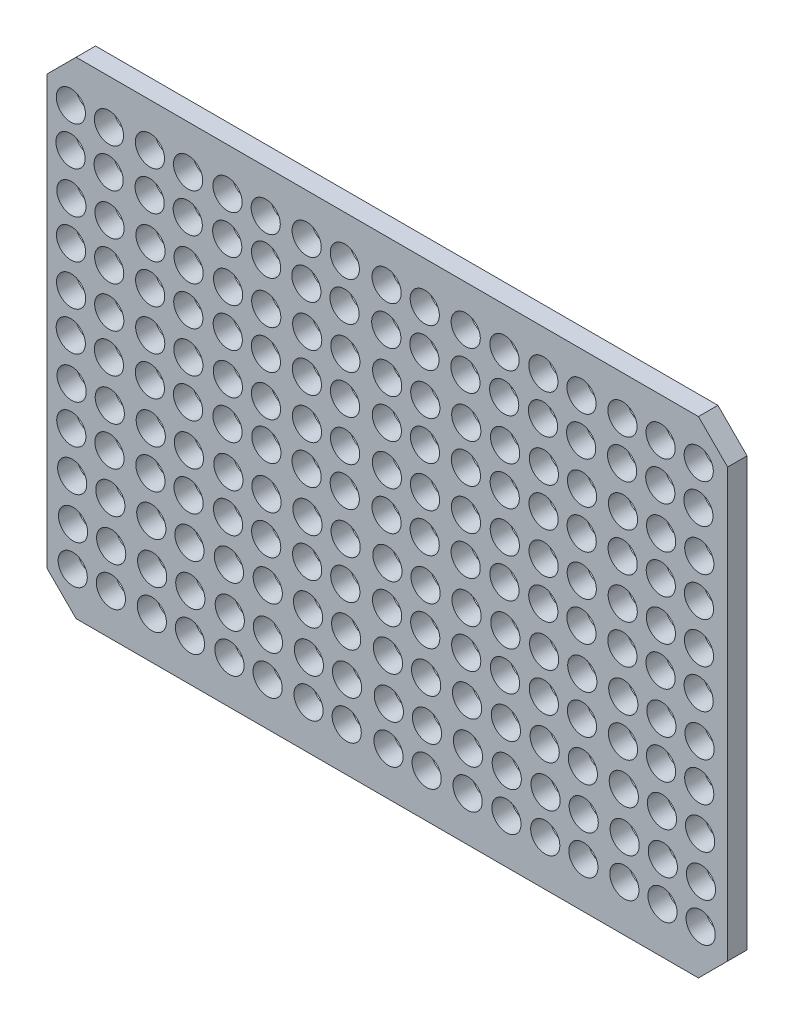
SolidWorks part; units mm, degrees
ref_plane "前视基准面" through (0, 0, 0) normal (0, 0, 1) x (1, 0, 0)
ref_plane "上视基准面" through (0, 0, 0) normal (0, 1, 0) x (1, 0, 0)
ref_plane "右视基准面" through (0, 0, 0) normal (1, 0, 0) x (0, 0, -1)
sketch "草图1" plane through (0, 0, 0) normal (0, 0, 1) x (1, 0, 0)
  line L1 (-35, 25) -> (35, 25)
  line L2 (-35, 25) -> (-35, -25)
  line L3 (-35, -25) -> (35, -25)
  line L4 (35, 25) -> (35, -25)
  line L5 (-35, 25) -> (35, -25) construction
  line L6 (-35, -25) -> (35, 25) construction
  point P0 (0, 0)
  dimension "D1" = 70
  dimension "D2" = 50
extrude "凸台-拉伸1" add sketch "草图1" along normal blind 2
sketch "草图2" plane through (0, 0, 2) normal (0, 0, 1) x (1, 0, 0)
  circle A0 centre (-32.5411, 20.4472) radius 1.5
  circle A1 centre (-28.6188, 20.4472) radius 1.5
  circle A2 centre (-24.4059, 20.5198) radius 1.5
  circle A3 centre (-20.4835, 20.5198) radius 1.5
  circle A4 centre (-16.4239, 20.6148) radius 1.5
  circle A5 centre (-12.5015, 20.6148) radius 1.5
  circle A6 centre (-8.2886, 20.6874) radius 1.5
  circle A7 centre (-4.3662, 20.6874) radius 1.5
  circle A8 centre (-0.0686, 20.6902) radius 1.5
  circle A9 centre (3.8537, 20.6902) radius 1.5
  circle A10 centre (8.0667, 20.7629) radius 1.5
  circle A11 centre (12.0577, 20.7629) radius 1.5
  circle A12 centre (16.0486, 20.8578) radius 1.5
  circle A13 centre (19.971, 20.8578) radius 1.5
  circle A14 centre (24.1839, 20.9305) radius 1.5
  circle A15 centre (28.1063, 20.9305) radius 1.5
  circle A16 centre (32.0287, 20.883) radius 1.5
  circle A17 centre (-32.5755, 16.4284) radius 1.5
  circle A18 centre (-28.6531, 16.4284) radius 1.5
  circle A19 centre (-24.4402, 16.5011) radius 1.5
  circle A20 centre (-20.5178, 16.5011) radius 1.5
  circle A21 centre (-16.4582, 16.596) radius 1.5
  circle A22 centre (-12.4632, 16.7413) radius 1.5
  circle A23 centre (-8.3229, 16.6687) radius 1.5
  circle A24 centre (-4.4005, 16.6687) radius 1.5
  circle A25 centre (-0.1029, 16.6715) radius 1.5
  circle A26 centre (3.8194, 16.6715) radius 1.5
  circle A27 centre (8.0324, 16.7441) radius 1.5
  circle A28 centre (12.0233, 16.7441) radius 1.5
  circle A29 centre (16.0143, 16.8391) radius 1.5
  circle A30 centre (19.9367, 16.8391) radius 1.5
  circle A31 centre (24.1496, 16.9117) radius 1.5
  circle A32 centre (28.072, 16.9117) radius 1.5
  circle A33 centre (31.9944, 16.8642) radius 1.5
  circle A34 centre (-32.4857, 12.1911) radius 1.5
  circle A35 centre (-28.5633, 12.1911) radius 1.5
  circle A36 centre (-24.3504, 12.2637) radius 1.5
  circle A37 centre (-20.428, 12.2637) radius 1.5
  circle A38 centre (-16.3684, 12.3587) radius 1.5
  circle A39 centre (-12.446, 12.3587) radius 1.5
  circle A40 centre (-8.2331, 12.4313) radius 1.5
  circle A41 centre (-4.3107, 12.4313) radius 1.5
  circle A42 centre (-0.0131, 12.4341) radius 1.5
  circle A43 centre (3.9092, 12.4341) radius 1.5
  circle A44 centre (8.1221, 12.5068) radius 1.5
  circle A45 centre (12.1131, 12.5068) radius 1.5
  circle A46 centre (16.1041, 12.6017) radius 1.5
  circle A47 centre (20.0265, 12.6017) radius 1.5
  circle A48 centre (24.2394, 12.6744) radius 1.5
  circle A49 centre (28.1618, 12.6744) radius 1.5
  circle A50 centre (32.0842, 12.6269) radius 1.5
  circle A51 centre (-32.52, 8.1723) radius 1.5
  circle A52 centre (-28.5976, 8.1723) radius 1.5
  circle A53 centre (-24.3847, 8.2449) radius 1.5
  circle A54 centre (-20.4623, 8.2449) radius 1.5
  circle A55 centre (-16.4027, 8.3399) radius 1.5
  circle A56 centre (-12.4803, 8.3399) radius 1.5
  circle A57 centre (-8.2674, 8.4126) radius 1.5
  circle A58 centre (-4.345, 8.4126) radius 1.5
  circle A59 centre (-0.0474, 8.4154) radius 1.5
  circle A60 centre (3.8749, 8.4154) radius 1.5
  circle A61 centre (8.0878, 8.488) radius 1.5
  circle A62 centre (12.0788, 8.488) radius 1.5
  circle A63 centre (16.0698, 8.583) radius 1.5
  circle A64 centre (19.9922, 8.583) radius 1.5
  circle A65 centre (24.2051, 8.6556) radius 1.5
  circle A66 centre (28.1275, 8.6556) radius 1.5
  circle A67 centre (32.0498, 8.6081) radius 1.5
  circle A68 centre (-32.5134, 3.9709) radius 1.5
  circle A69 centre (-28.591, 3.9709) radius 1.5
  circle A70 centre (-24.3781, 4.0435) radius 1.5
  circle A71 centre (-20.4557, 4.0435) radius 1.5
  circle A72 centre (-16.3961, 4.1385) radius 1.5
  circle A73 centre (-12.4738, 4.1385) radius 1.5
  circle A74 centre (-8.2608, 4.2112) radius 1.5
  circle A75 centre (-4.3385, 4.2112) radius 1.5
  circle A76 centre (-0.0409, 4.214) radius 1.5
  circle A77 centre (3.8815, 4.214) radius 1.5
  circle A78 centre (8.0944, 4.2866) radius 1.5
  circle A79 centre (12.0854, 4.2866) radius 1.5
  circle A80 centre (16.0764, 4.3816) radius 1.5
  circle A81 centre (19.9988, 4.3816) radius 1.5
  circle A82 centre (24.2117, 4.4542) radius 1.5
  circle A83 centre (28.134, 4.4542) radius 1.5
  circle A84 centre (32.0564, 4.4067) radius 1.5
  circle A85 centre (-32.5477, -0.0478) radius 1.5
  circle A86 centre (-28.6253, -0.0478) radius 1.5
  circle A87 centre (-24.4124, 0.0248) radius 1.5
  circle A88 centre (-20.4901, 0.0248) radius 1.5
  circle A89 centre (-16.4304, 0.1198) radius 1.5
  circle A90 centre (-12.4354, 0.265) radius 1.5
  circle A91 centre (-8.2952, 0.1924) radius 1.5
  circle A92 centre (-4.3728, 0.1924) radius 1.5
  circle A93 centre (-0.0752, 0.1952) radius 1.5
  circle A94 centre (3.8472, 0.1952) radius 1.5
  circle A95 centre (8.0601, 0.2679) radius 1.5
  circle A96 centre (12.0511, 0.2679) radius 1.5
  circle A97 centre (16.0421, 0.3628) radius 1.5
  circle A98 centre (19.9644, 0.3628) radius 1.5
  circle A99 centre (24.1774, 0.4355) radius 1.5
  circle A100 centre (28.0997, 0.4355) radius 1.5
  circle A101 centre (32.0221, 0.388) radius 1.5
  circle A102 centre (-32.4579, -4.2852) radius 1.5
  circle A103 centre (-28.5355, -4.2852) radius 1.5
  circle A104 centre (-24.3226, -4.2126) radius 1.5
  circle A105 centre (-20.4003, -4.2126) radius 1.5
  circle A106 centre (-16.3407, -4.1176) radius 1.5
  circle A107 centre (-12.4183, -4.1176) radius 1.5
  circle A108 centre (-8.2054, -4.045) radius 1.5
  circle A109 centre (-4.283, -4.045) radius 1.5
  circle A110 centre (0.0146, -4.0421) radius 1.5
  circle A111 centre (3.937, -4.0421) radius 1.5
  circle A112 centre (8.1499, -3.9695) radius 1.5
  circle A113 centre (12.1409, -3.9695) radius 1.5
  circle A114 centre (16.1319, -3.8745) radius 1.5
  circle A115 centre (20.0542, -3.8745) radius 1.5
  circle A116 centre (24.2672, -3.8019) radius 1.5
  circle A117 centre (28.1895, -3.8019) radius 1.5
  circle A118 centre (32.1119, -3.8494) radius 1.5
  circle A119 centre (-32.4922, -8.304) radius 1.5
  circle A120 centre (-28.5699, -8.304) radius 1.5
  circle A121 centre (-24.3569, -8.2313) radius 1.5
  circle A122 centre (-20.4346, -8.2313) radius 1.5
  circle A123 centre (-16.375, -8.1363) radius 1.5
  circle A124 centre (-12.4526, -8.1363) radius 1.5
  circle A125 centre (-8.2397, -8.0637) radius 1.5
  circle A126 centre (-4.3173, -8.0637) radius 1.5
  circle A127 centre (-0.0197, -8.0609) radius 1.5
  circle A128 centre (3.9027, -8.0609) radius 1.5
  circle A129 centre (8.1156, -7.9883) radius 1.5
  circle A130 centre (12.1066, -7.9883) radius 1.5
  circle A131 centre (16.0976, -7.8933) radius 1.5
  circle A132 centre (20.0199, -7.8933) radius 1.5
  circle A133 centre (24.2328, -7.8206) radius 1.5
  circle A134 centre (28.1552, -7.8206) radius 1.5
  circle A135 centre (32.0776, -7.8681) radius 1.5
  circle A136 centre (-32.4024, -12.4931) radius 1.5
  circle A137 centre (-28.4801, -12.4931) radius 1.5
  circle A138 centre (-24.2672, -12.4205) radius 1.5
  circle A139 centre (-20.3448, -12.4205) radius 1.5
  circle A140 centre (-16.2852, -12.3255) radius 1.5
  circle A141 centre (-12.2902, -12.1802) radius 1.5
  circle A142 centre (-8.1499, -12.2529) radius 1.5
  circle A143 centre (-4.2275, -12.2529) radius 1.5
  circle A144 centre (0.0701, -12.2501) radius 1.5
  circle A145 centre (3.9925, -12.2501) radius 1.5
  circle A146 centre (8.2054, -12.1774) radius 1.5
  circle A147 centre (12.1964, -12.1774) radius 1.5
  circle A148 centre (16.1873, -12.0825) radius 1.5
  circle A149 centre (20.1097, -12.0825) radius 1.5
  circle A150 centre (24.3226, -12.0098) radius 1.5
  circle A151 centre (28.245, -12.0098) radius 1.5
  circle A152 centre (32.1674, -12.0573) radius 1.5
  circle A153 centre (-32.3126, -16.7305) radius 1.5
  circle A154 centre (-28.3903, -16.7305) radius 1.5
  circle A155 centre (-24.1774, -16.6578) radius 1.5
  circle A156 centre (-20.255, -16.6578) radius 1.5
  circle A157 centre (-16.1954, -16.5629) radius 1.5
  circle A158 centre (-12.273, -16.5629) radius 1.5
  circle A159 centre (-8.0601, -16.4902) radius 1.5
  circle A160 centre (-4.1377, -16.4902) radius 1.5
  circle A161 centre (0.1599, -16.4874) radius 1.5
  circle A162 centre (4.0822, -16.4874) radius 1.5
  circle A163 centre (8.2952, -16.4148) radius 1.5
  circle A164 centre (12.2862, -16.4148) radius 1.5
  circle A165 centre (16.2771, -16.3198) radius 1.5
  circle A166 centre (20.1995, -16.3198) radius 1.5
  circle A167 centre (24.4124, -16.2472) radius 1.5
  circle A168 centre (28.3348, -16.2472) radius 1.5
  circle A169 centre (32.2572, -16.2947) radius 1.5
  circle A170 centre (-32.347, -20.7492) radius 1.5
  circle A171 centre (-28.4246, -20.7492) radius 1.5
  circle A172 centre (-24.2117, -20.6766) radius 1.5
  circle A173 centre (-20.2893, -20.6766) radius 1.5
  circle A174 centre (-16.2297, -20.5816) radius 1.5
  circle A175 centre (-12.3073, -20.5816) radius 1.5
  circle A176 centre (-8.0944, -20.509) radius 1.5
  circle A177 centre (-4.172, -20.509) radius 1.5
  circle A178 centre (0.1256, -20.5062) radius 1.5
  circle A179 centre (4.0479, -20.5062) radius 1.5
  circle A180 centre (8.2608, -20.4335) radius 1.5
  circle A181 centre (12.2518, -20.4335) radius 1.5
  circle A182 centre (16.2428, -20.3386) radius 1.5
  circle A183 centre (20.1652, -20.3386) radius 1.5
  circle A184 centre (24.3781, -20.2659) radius 1.5
  circle A185 centre (28.3005, -20.2659) radius 1.5
  circle A186 centre (32.2229, -20.3134) radius 1.5
extrude "切除-拉伸1" cut sketch "草图2" against normal through all
chamfer "倒角1" distance 3 4 edges at (35, -25, 1) (-35, -25, 1) (-35, 25, 1) (35, 25, 1)
